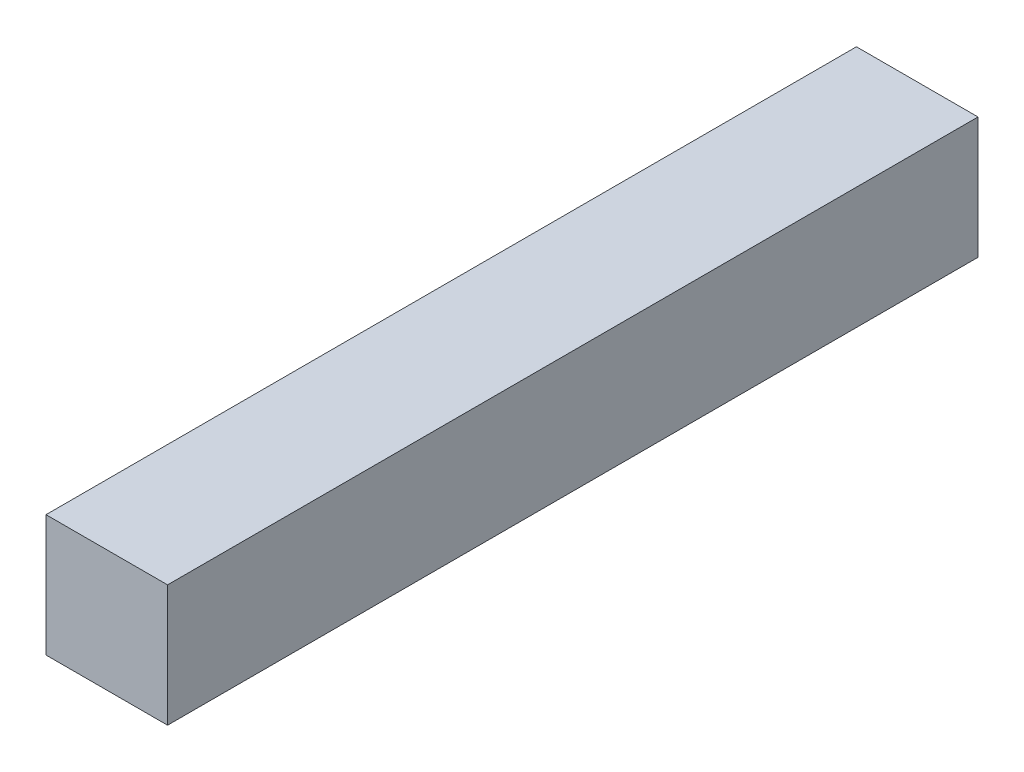
SolidWorks part; units mm, degrees
material "Plain Carbon Steel"
ref_plane "Front Plane" through (0, 0, 0) normal (0, 0, 1) x (1, 0, 0)
ref_plane "Top Plane" through (0, 0, 0) normal (0, 1, 0) x (1, 0, 0)
ref_plane "Right Plane" through (0, 0, 0) normal (1, 0, 0) x (0, 0, -1)
sketch "Sketch1" plane through (0, 0, 0) normal (0, 0, 1) x (1, 0, 0)
  line L1 (-2.3813, -2.3813) -> (2.3812, -2.3813)
  line L2 (-2.3813, -2.3813) -> (-2.3813, 2.3812)
  line L3 (-2.3813, 2.3812) -> (2.3812, 2.3812)
  line L4 (2.3812, -2.3813) -> (2.3812, 2.3812)
  line L5 (-2.3813, -2.3813) -> (2.3812, 2.3812) construction
  line L6 (-2.3813, 2.3812) -> (2.3812, -2.3813) construction
  point P0 (0, 0)
  dimension "D1" = 4.7625
  dimension "D2" = 4.7625
extrude "Boss-Extrude1" add sketch "Sketch1" along normal blind 31.75
